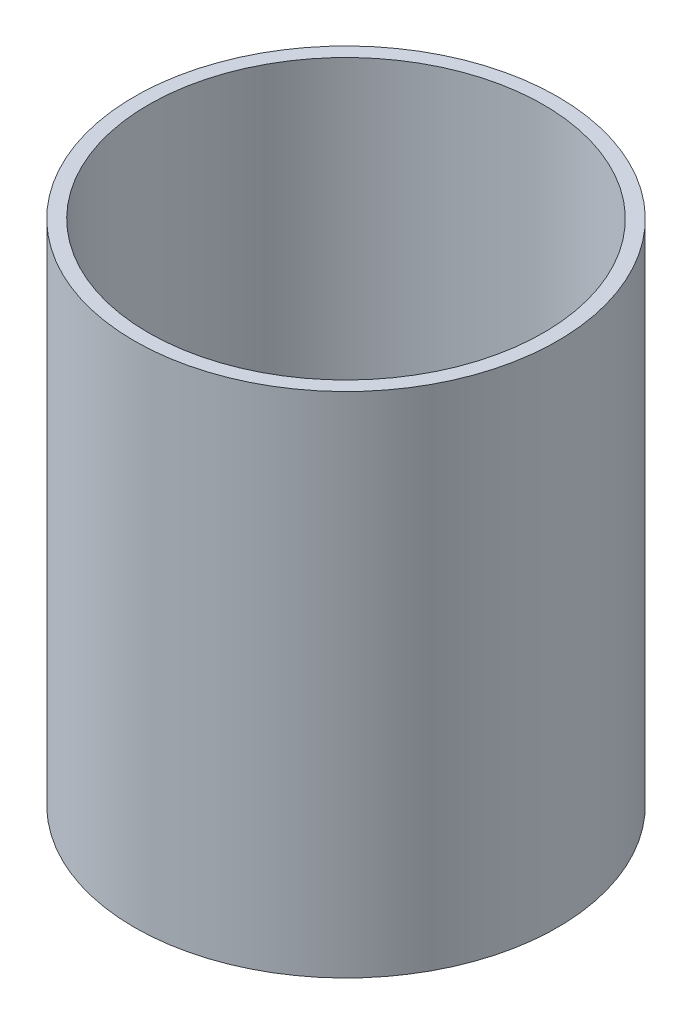
SolidWorks part; units mm, degrees
ref_plane "Alzado" through (0, 0, 0) normal (0, 0, 1) x (1, 0, 0)
ref_plane "Planta" through (0, 0, 0) normal (0, 1, 0) x (1, 0, 0)
ref_plane "Vista lateral" through (0, 0, 0) normal (1, 0, 0) x (0, 0, -1)
sketch "Croquis1" plane through (0, 0, 0) normal (0, 1, 0) x (1, 0, 0)
  circle A0 centre (0, 0) radius 150
  dimension "D1" = 300
extrude "Saliente-Extruir1" add sketch "Croquis1" along normal blind 360
sketch "Croquis2" plane through (0, 360, 0) normal (0, 1, 0) x (1, 0, 0)
  circle A2 centre (0, 0) radius 140
  circle A3 centre (0, 0) radius 140
  dimension "D1" = 10
extrude "Cortar-Extruir1" cut sketch "Croquis2" against normal blind 350
